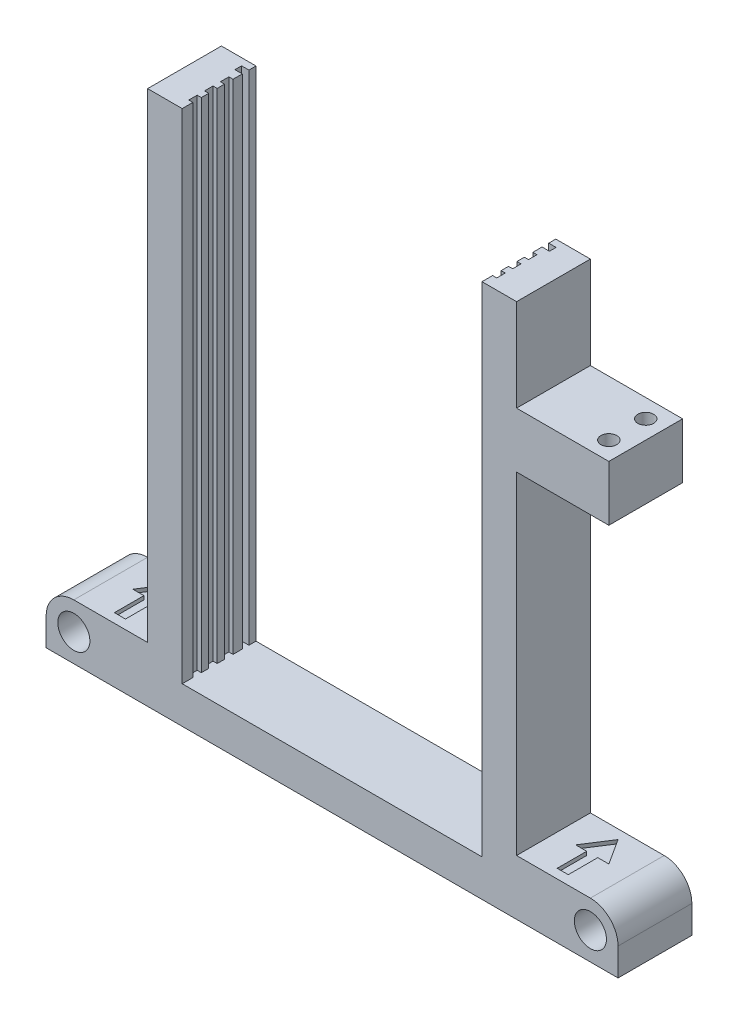
SolidWorks part; units mm, degrees
material "ABS"
ref_plane "Front Plane" through (0, 0, 0) normal (0, 0, 1) x (1, 0, 0)
ref_plane "Top Plane" through (0, 0, 0) normal (0, 1, 0) x (1, 0, 0)
ref_plane "Right Plane" through (0, 0, 0) normal (1, 0, 0) x (0, 0, -1)
sketch "Sketch1" plane through (0, 0, 0) normal (0, 0, 1) x (1, 0, 0)
  line L0 (-77.5, 0) -> (77.5, 0)
  line L1 (-70, 7.5) -> (70, 7.5) construction
  line L2 (-77.5, 0) -> (-77.5, 7.5)
  line L3 (-70, 15) -> (-50, 15)
  line L4 (-50, 15) -> (-50, 145)
  line L5 (-50, 145) -> (50, 145)
  line L6 (50, 145) -> (50, 15)
  line L7 (50, 15) -> (70, 15)
  line L8 (77.5, 7.5) -> (77.5, 0)
  circle A0 centre (-70, 7.5) radius 4.35
  circle A1 centre (70, 7.5) radius 4.35
  arc A2 (-77.5, 7.5) -> (-70, 15) centre (-70, 7.5) cw
  arc A3 (70, 15) -> (77.5, 7.5) centre (70, 7.5) cw
  point P2 (0, 0)
  point P6 (0, 145)
  point P8 (0, 7.5)
  dimension "D2" = 8.7
  dimension "D1" = 140
  dimension "D3" = 155
  dimension "D4" = 7.5
  dimension "D5" = 130
  dimension "D6" = 100
extrude "Boss-Extrude1" add sketch "Sketch1" along normal mid plane 20 contours L4 L5 L6 L7 A3 L8 L0 L2 A2 L3
sketch "Sketch2" plane through (0, 145, 0) normal (0, 1, 0) x (1, 0, 0)
  line L0 (-40.625, -10) -> (-40.625, 6.28)
  line L1 (50, -10) -> (-50, -10) construction
  line L2 (-40.625, 6.28) -> (-42.625, 6.28)
  line L3 (-42.625, 6.28) -> (-42.625, 8.08)
  line L4 (-42.625, 8.08) -> (-40.625, 8.08)
  line L5 (-40.625, 8.08) -> (-40.625, 10)
  line L6 (50, 10) -> (-50, 10) construction
  line L7 (-40.625, 10) -> (40.625, 10)
  line L8 (40.625, 10) -> (40.625, 8.08)
  line L9 (40.625, 8.08) -> (42.625, 8.08)
  line L10 (42.625, 8.08) -> (42.625, 6.28)
  line L11 (42.625, 6.28) -> (40.625, 6.28)
  line L12 (40.625, 6.28) -> (40.625, -10)
  line L13 (40.625, -10) -> (-40.625, -10)
  point P6 (0, 10)
  dimension "D1" = 1.8
  dimension "D2" = 85.25
  dimension "D3" = 81.25
  dimension "D4" = 1.92
extrude "Cut-Extrude1" cut sketch "Sketch2" against normal offset from surface (135 mm away) 10 up to face at (0, 0, 0)
sketch "Sketch3" plane through (0, 145, 0) normal (0, 1, 0) x (1, 0, 0)
  line L0 (-42.625, 6.28) -> (-40.625, 6.28) construction
  line L1 (41.75, 3.78) -> (-41.75, 3.78)
  line L2 (41.75, 3.78) -> (41.75, 1.48)
  line L3 (41.75, 1.48) -> (-41.75, 1.48)
  line L4 (-41.75, 3.78) -> (-41.75, 1.48)
  point P4 (0, 1.48)
  dimension "D1" = 2.3
  dimension "D2" = 2.5
  dimension "D3" = 83.5
extrude "Cut-Extrude2" cut sketch "Sketch3" against normal up to surface (135 mm away) up to face at (0, 10, -4.7867)
pattern_linear "LPattern1" count 3 spacing 4.3 along (0, 0, 1) of "Cut-Extrude2"
sketch "Sketch4" plane through (0, 15, 0) normal (0, 1, 0) x (1, 0, 0)
  line L0 (60, 7.5) -> (55.5, 0.5)
  line L1 (55.5, 0.5) -> (58.5, 0.5)
  line L2 (58.5, 0.5) -> (58.5, -7.5)
  line L3 (58.5, -7.5) -> (61.5, -7.5)
  line L4 (61.5, -7.5) -> (61.5, 0.5)
  line L5 (61.5, 0.5) -> (64.5, 0.5)
  line L6 (64.5, 0.5) -> (60, 7.5)
  line L7 (70, 10) -> (50, 10) construction
  line L8 (60, -7.5) -> (60, 7.5) construction
  line L9 (70, -10) -> (70, 10) construction
  point P2 (60, -7.5)
  point P8 (60, 0)
  point P11 (60, 10)
  point P15 (70, 0)
  dimension "D1" = 3
  dimension "D2" = 3
  dimension "D3" = 8
  dimension "D4" = 15
extrude "Cut-Extrude3" cut sketch "Sketch4" against normal blind 1
mirror "Mirror1" about plane through (0, 0, 0) normal (1, 0, 0) of "Cut-Extrude3"
sketch "Sketch5" plane through (0, 0, -10) normal (0, 0, -1) x (-1, 0, 0)
  line L0 (-50, 15) -> (-50, 145) construction
  line L1 (-50, 120) -> (-75, 120)
  line L2 (-50, 120) -> (-50, 105)
  line L3 (-50, 105) -> (-75, 105)
  line L4 (-75, 120) -> (-75, 105)
  dimension "D1" = 25
  dimension "D2" = 25
  dimension "D3" = 15
extrude "Boss-Extrude2" add sketch "Sketch5" against normal up to surface (20 mm away) up to face at (0, 48.4362, 10)
hole_wizard "#6 Clearance Hole1" positions "Sketch6" profile "Sketch8" hole size "#6" standard "ANSI Inch"
sketch "Sketch6" plane through (0, 120, 0) normal (0, 1, 0) x (1, 0, 0)
  line L0 (70, -5) -> (70, 5) construction
  line L1 (75, -10) -> (75, 10) construction
  point P0 (70, 5)
  point P2 (70, -5)
  point P8 (70, 0)
  point P11 (75, 0)
  dimension "D1" = 10
  dimension "D2" = 5
sketch "Sketch8" plane through (70, 120, -5) normal (1, 0, 0) x (0, 0, 1)
  line L0 (0, 0) -> (0, 21.2934)
  line L1 (0, 21.2934) -> (2.1526, 20)
  line L2 (2.1526, 20) -> (2.1526, 0)
  line L5 (2.1526, 0) -> (0, 0)
  line L10 (0, 21.2934) -> (-2.1527, 20) construction
  line L11 (0, -6.35) -> (0, 107.95) construction
  dimension "Hole Dia." = 4.3053
  dimension "Hole Depth" = 20
  dimension "Drill Angle" = 118
